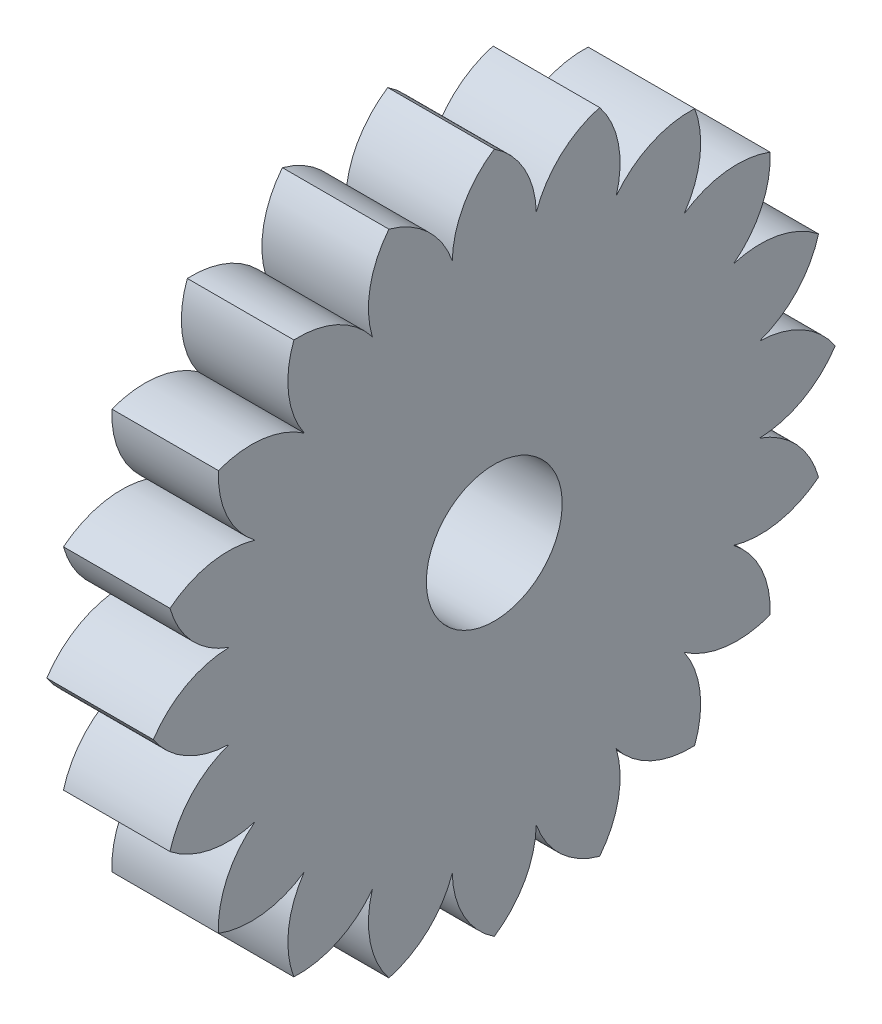
SolidWorks part; units mm, degrees
ref_plane "정면" through (0, 0, 0) normal (0, 0, 1) x (1, 0, 0)
ref_plane "윗면" through (0, 0, 0) normal (0, 1, 0) x (1, 0, 0)
ref_plane "우측면" through (0, 0, 0) normal (1, 0, 0) x (0, 0, -1)
sketch "스케치1" plane through (0, 0, 0) normal (1, 0, 0) x (0, 0, -1)
  line L0 (0, 0) -> (0, 34.3447) construction
  line L1 (0, 0) -> (43.6669, 0) construction
  line L2 (1.5785, 0) -> (1.5785, 9.8746) construction
  line L3 (0, 0) -> (0, 12.8) construction
  circle A2 centre (0, 0) radius 10 construction
  arc A3 (0, 12.8) -> (1.5785, 9.8746) centre (-1.9215, 9.8746) cw
  arc A4 (0, 12.8) -> (-1.5785, 9.8746) centre (1.9215, 9.8746) ccw
  arc A5 (1.5785, 9.8746) -> (-1.5785, 9.8746) centre (0, 0) cw
  dimension "D1" = 12.8
  dimension "D2" = 10
  dimension "D3" = 3.5
extrude "보스-돌출1" add sketch "스케치1" along normal blind 4 contours A5 A4 A3
pattern_circular "원형 패턴1" count 20 over 360 about axis through (0, 0, 0) along (1, 0, 0) of "보스-돌출1"
sketch "스케치2" plane through (0, 0, 0) normal (-1, 0, 0) x (0, 0, 1)
  circle A0 centre (0, 0) radius 2.25 construction
  circle A1 centre (0, 0) radius 2.25 construction
  circle A2 centre (0, 0) radius 2.55
  dimension "D1" = 0.3
extrude "컷-돌출1" cut sketch "스케치2" against normal through all both and the other way through all
